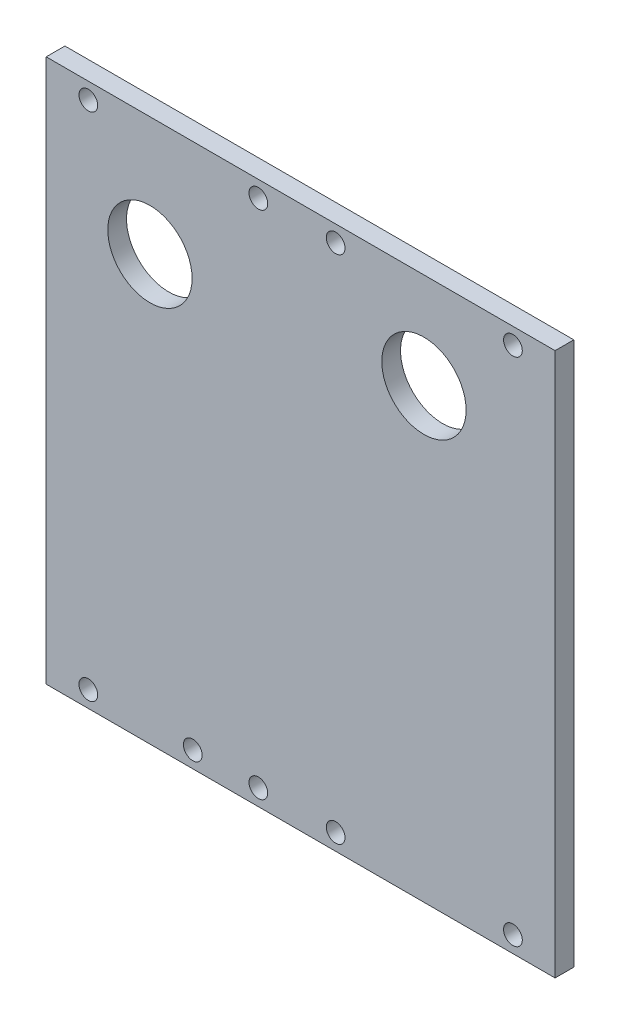
SolidWorks part; units mm, degrees
ref_plane "Front Plane" through (0, 0, 0) normal (0, 0, 1) x (1, 0, 0)
ref_plane "Top Plane" through (0, 0, 0) normal (0, 1, 0) x (1, 0, 0)
ref_plane "Right Plane" through (0, 0, 0) normal (1, 0, 0) x (0, 0, -1)
sketch "Sketch1" plane through (0, 0, 0) normal (0, 0, 1) x (1, 0, 0)
  line L1 (-54.325, -58) -> (54.325, -58)
  line L2 (-54.325, -58) -> (-54.325, 58)
  line L3 (-54.325, 58) -> (54.325, 58)
  line L4 (54.325, -58) -> (54.325, 58)
  line L5 (-54.325, -58) -> (54.325, 58) construction
  line L6 (-54.325, 58) -> (54.325, -58) construction
  point P0 (0, 0)
  dimension "D1" = 108.65
  dimension "120" = 116
extrude "Boss-Extrude1" add sketch "Sketch1" along normal blind 4
sketch "Sketch2" plane through (0, 0, 4) normal (0, 0, 1) x (1, 0, 0)
  line L0 (54.325, 58) -> (-54.325, 58) construction
  line L1 (54.325, -58) -> (54.325, 58) construction
  circle A0 centre (26.325, 37.5) radius 9
  circle A1 centre (26.325, 37.5) radius 20 construction
  circle A3 centre (-32.175, 32.6) radius 9
  dimension "D1" = 18
  dimension "D3" = 40
  dimension "D4" = 28
  dimension "D5" = 25.4
  dimension "D2" = 20.5
  dimension "D6" = 58.5
extrude "Cut-Extrude1" cut sketch "Sketch2" against normal through all
sketch "Sketch3" plane through (54.325, 0, 0) normal (1, 0, 0) x (0, 0, -1)
  line L0 (-2, 58) -> (-2, 41.1774) construction
  line L1 (-4, 58) -> (0, 58) construction
  line L2 (0, 0) -> (7, 0) construction
  line L3 (7, 51) -> (0, 51) construction
  line L4 (0, -58) -> (0, 58) construction
  line L5 (-4, 54.5) -> (-16, 54.5)
  line L6 (0, 47.5) -> (12, 47.5)
  line L7 (0, 47.5) -> (0, 54.5)
  line L8 (0, 54.5) -> (12, 54.5)
  line L9 (12, 47.5) -> (12, 54.5)
  line L10 (-16, 47.5) -> (-16, 54.5)
  line L11 (-4, 47.5) -> (-16, 47.5)
  line L12 (-4, 47.5) -> (-4, 54.5)
  line L13 (0, -54.5) -> (12, -54.5)
  line L14 (12, -47.5) -> (12, -54.5)
  line L15 (0, -47.5) -> (12, -47.5)
  line L16 (0, -47.5) -> (0, -54.5)
  line L17 (-4, -47.5) -> (-4, -54.5)
  line L18 (-4, -47.5) -> (-16, -47.5)
  line L19 (-16, -47.5) -> (-16, -54.5)
  line L20 (-4, -54.5) -> (-16, -54.5)
  circle A0 centre (7, 51) radius 2
  circle A1 centre (-11, 51) radius 2
  circle A2 centre (7, -51) radius 2
  circle A3 centre (-11, -51) radius 2
  point P17 (0, 51)
  dimension "D2" = 4
  dimension "D1" = 7
  dimension "D3" = 7
  dimension "D4" = 7
  dimension "D5" = 12
extrude "Boss-Extrude2" [suppressed] add sketch "Sketch3" against normal blind 4
fillet "Fillet1" [suppressed] radius 4
fillet "Fillet2" [suppressed] radius 2
sketch "Sketch4" plane through (0, 0, 4) normal (0, 0, 1) x (1, 0, 0)
  line L0 (-54.325, -58) -> (54.325, -58) construction
  line L1 (-54.325, 58) -> (-50.325, 58) construction
  line L2 (-54.325, 58) -> (-54.325, -58) construction
  line L3 (-54.325, -58) -> (-50.325, -58) construction
  line L4 (-50.325, 58) -> (-50.325, -58) construction
  line L5 (-45.325, 51) -> (-50.325, 51) construction
  line L6 (-50.325, 54.5) -> (-40.325, 54.5) construction
  line L7 (-50.325, 54.5) -> (-50.325, 47.5) construction
  line L8 (-50.325, 47.5) -> (-40.325, 47.5) construction
  line L9 (-40.325, 54.5) -> (-40.325, 47.5) construction
  line L10 (-50.325, 0) -> (0, 0) construction
  line L11 (-14.025, 58) -> (-14.025, -58) construction
  line L12 (-18.025, 58) -> (-18.025, -58) construction
  line L13 (-18.025, -58) -> (-14.025, -58) construction
  line L14 (-18.025, 58) -> (-14.025, 58) construction
  line L15 (-14.025, 54.5) -> (-4.025, 54.5) construction
  line L16 (-14.025, 47.5) -> (-4.025, 47.5) construction
  line L17 (-4.025, 54.5) -> (-4.025, 47.5) construction
  line L18 (-9.025, 51) -> (-23.025, 51) construction
  line L19 (54.325, 58) -> (-54.325, 58) construction
  line L20 (-16.025, 58) -> (-16.025, 65.6289) construction
  line L21 (-9.025, 54.5) -> (7.475, 54.5) construction
  line L22 (54.325, -58) -> (54.325, 58) construction
  circle A0 centre (-45.325, 51) radius 2 construction
  circle A1 centre (-45.325, -51) radius 2 construction
  circle A2 centre (-9.025, 51) radius 2 construction
  circle A3 centre (-9.025, -51) radius 2 construction
  circle A4 centre (-23.025, 51) radius 2 construction
  circle A5 centre (-23.025, -51) radius 2 construction
  circle A6 centre (-45.325, 54.5) radius 2
  circle A7 centre (-45.325, -54.5) radius 2
  circle A8 centre (-23.025, 54.5) radius 2 construction
  circle A9 centre (-9.025, 54.5) radius 2
  circle A10 centre (-9.025, -54.5) radius 2
  circle A11 centre (-23.025, -54.5) radius 2
  circle A12 centre (7.475, 54.5) radius 2
  circle A13 centre (7.475, -54.5) radius 2
  circle A14 centre (45.325, 54.5) radius 2
  circle A15 centre (45.325, -54.5) radius 2
  point P15 (-50.325, 51)
  point P56 (0, 0)
  dimension "D1" = 4
  dimension "D2" = 4
  dimension "D3" = 7
  dimension "D4" = 10
  dimension "D5" = 5
  dimension "D6" = 7
  dimension "D8" = 36.3
  dimension "D9" = 5
  dimension "D10" = 3.5
  dimension "D11" = 3.5
  dimension "D12" = 16.5
  dimension "D13" = 9
  dimension "D7" = 2
extrude "Cut-Extrude2" cut sketch "Sketch4" against normal through all
equation "\"D11@Sketch4\"=\"D6@Sketch4\"/2"
